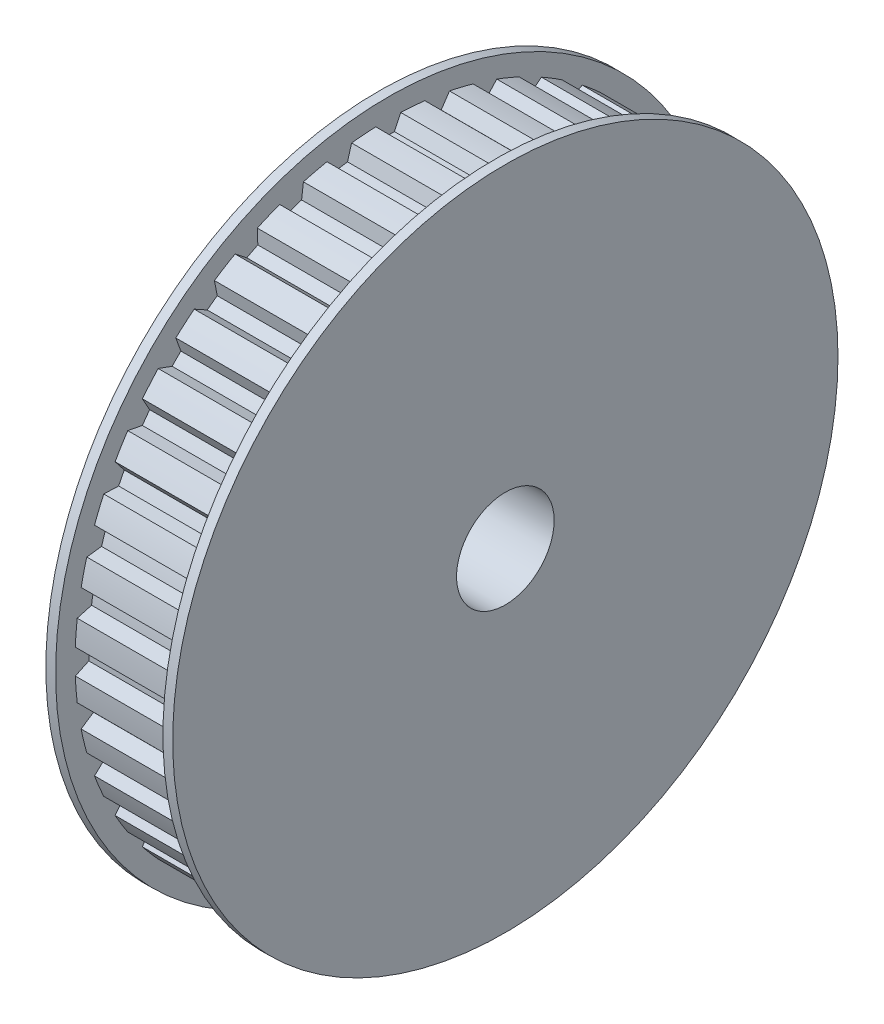
SolidWorks part; units mm, degrees
ref_plane "Front Plane" through (0, 0, 0) normal (0, 0, 1) x (1, 0, 0)
ref_plane "Top Plane" through (0, 0, 0) normal (0, 1, 0) x (1, 0, 0)
ref_plane "Right Plane" through (0, 0, 0) normal (1, 0, 0) x (0, 0, -1)
sketch "Sketch1" plane through (0, 0, 0) normal (1, 0, 0) x (0, 0, -1)
  line L0 (0, 32.085) -> (0, 0) construction
  circle A0 centre (0, 0) radius 32.085
  circle A1 centre (0, 0) radius 5
  point P19 (0, 0)
  dimension "D1" = 64.17
  dimension "D2" = 10
extrude "Boss-Extrude1" add sketch "Sketch1" along normal blind 11
sketch "Sketch2" plane through (0, 0, 0) normal (-1, 0, 0) x (0, 0, 1)
  line L0 (0, 0) -> (0, 32.085) construction
  line L1 (1.279, 32.0595) -> (0.635, 30.6784)
  line L2 (-1.279, 32.0595) -> (-0.635, 30.6784)
  line L3 (6.2784, 31.4647) -> (5.4263, 30.2014)
  line L4 (3.752, 31.8649) -> (4.172, 30.4001)
  line L5 (11.1233, 30.0952) -> (10.084, 28.9807)
  line L6 (8.6906, 30.8856) -> (8.8763, 29.3731)
  line L7 (15.6943, 27.9846) -> (14.4935, 27.0464)
  line L8 (13.4151, 29.1459) -> (13.362, 27.6229)
  line L9 (19.8788, 25.1849) -> (18.546, 24.4462)
  line L10 (17.8094, 26.6884) -> (17.5186, 25.1926)
  line L11 (23.5738, 21.7651) -> (22.1419, 21.2439)
  line L12 (21.7651, 23.5738) -> (21.2439, 22.1419)
  line L13 (26.6884, 17.8094) -> (25.1926, 17.5186)
  line L14 (25.1849, 19.8788) -> (24.4462, 18.546)
  line L15 (29.1459, 13.4151) -> (27.6229, 13.362)
  line L16 (27.9846, 15.6943) -> (27.0464, 14.4935)
  line L17 (30.8856, 8.6906) -> (29.3731, 8.8763)
  line L18 (30.0952, 11.1233) -> (28.9807, 10.084)
  line L19 (31.8649, 3.752) -> (30.4001, 4.172)
  line L20 (31.4647, 6.2784) -> (30.2014, 5.4263)
  line L21 (32.0595, -1.279) -> (30.6784, -0.635)
  line L22 (32.0595, 1.279) -> (30.6784, 0.635)
  line L23 (31.4647, -6.2784) -> (30.2014, -5.4263)
  line L24 (31.8649, -3.752) -> (30.4001, -4.172)
  line L25 (30.0952, -11.1233) -> (28.9807, -10.084)
  line L26 (30.8856, -8.6906) -> (29.3731, -8.8763)
  line L27 (27.9846, -15.6943) -> (27.0464, -14.4935)
  line L28 (29.1459, -13.4151) -> (27.6229, -13.362)
  line L29 (25.1849, -19.8788) -> (24.4462, -18.546)
  line L30 (26.6884, -17.8094) -> (25.1926, -17.5186)
  line L31 (21.7651, -23.5738) -> (21.2439, -22.1419)
  line L32 (23.5738, -21.7651) -> (22.1419, -21.2439)
  line L33 (17.8094, -26.6884) -> (17.5186, -25.1926)
  line L34 (19.8788, -25.1849) -> (18.546, -24.4462)
  line L35 (13.4151, -29.1459) -> (13.362, -27.6229)
  line L36 (15.6943, -27.9846) -> (14.4935, -27.0464)
  line L37 (8.6906, -30.8856) -> (8.8763, -29.3731)
  line L38 (11.1233, -30.0952) -> (10.084, -28.9807)
  line L39 (3.752, -31.8649) -> (4.172, -30.4001)
  line L40 (6.2784, -31.4647) -> (5.4263, -30.2014)
  line L41 (-1.279, -32.0595) -> (-0.635, -30.6784)
  line L42 (1.279, -32.0595) -> (0.635, -30.6784)
  line L43 (-6.2784, -31.4647) -> (-5.4263, -30.2014)
  line L44 (-3.752, -31.8649) -> (-4.172, -30.4001)
  line L45 (-11.1233, -30.0952) -> (-10.084, -28.9807)
  line L46 (-8.6906, -30.8856) -> (-8.8763, -29.3731)
  line L47 (-15.6943, -27.9846) -> (-14.4935, -27.0464)
  line L48 (-13.4151, -29.1459) -> (-13.362, -27.6229)
  line L49 (-19.8788, -25.1849) -> (-18.546, -24.4462)
  line L50 (-17.8094, -26.6884) -> (-17.5186, -25.1926)
  line L51 (-23.5738, -21.7651) -> (-22.1419, -21.2439)
  line L52 (-21.7651, -23.5738) -> (-21.2439, -22.1419)
  line L53 (-26.6884, -17.8094) -> (-25.1926, -17.5186)
  line L54 (-25.1849, -19.8788) -> (-24.4462, -18.546)
  line L55 (-29.1459, -13.4151) -> (-27.6229, -13.362)
  line L56 (-27.9846, -15.6943) -> (-27.0464, -14.4935)
  line L57 (-30.8856, -8.6906) -> (-29.3731, -8.8763)
  line L58 (-30.0952, -11.1233) -> (-28.9807, -10.084)
  line L59 (-31.8649, -3.752) -> (-30.4001, -4.172)
  line L60 (-31.4647, -6.2784) -> (-30.2014, -5.4263)
  line L61 (-32.0595, 1.279) -> (-30.6784, 0.635)
  line L62 (-32.0595, -1.279) -> (-30.6784, -0.635)
  line L63 (-31.4647, 6.2784) -> (-30.2014, 5.4263)
  line L64 (-31.8649, 3.752) -> (-30.4001, 4.172)
  line L65 (-30.0952, 11.1233) -> (-28.9807, 10.084)
  line L66 (-30.8856, 8.6906) -> (-29.3731, 8.8763)
  line L67 (-27.9846, 15.6943) -> (-27.0464, 14.4935)
  line L68 (-29.1459, 13.4151) -> (-27.6229, 13.362)
  line L69 (-25.1849, 19.8788) -> (-24.4462, 18.546)
  line L70 (-26.6884, 17.8094) -> (-25.1926, 17.5186)
  line L71 (-21.7651, 23.5738) -> (-21.2439, 22.1419)
  line L72 (-23.5738, 21.7651) -> (-22.1419, 21.2439)
  line L73 (-17.8094, 26.6884) -> (-17.5186, 25.1926)
  line L74 (-19.8788, 25.1849) -> (-18.546, 24.4462)
  line L75 (-13.4151, 29.1459) -> (-13.362, 27.6229)
  line L76 (-15.6943, 27.9846) -> (-14.4935, 27.0464)
  line L77 (-8.6906, 30.8856) -> (-8.8763, 29.3731)
  line L78 (-11.1233, 30.0952) -> (-10.084, 28.9807)
  line L79 (-3.752, 31.8649) -> (-4.172, 30.4001)
  line L80 (-6.2784, 31.4647) -> (-5.4263, 30.2014)
  circle A0 centre (0, 0) radius 32.085 construction
  arc A1 (1.279, 32.0595) -> (-1.279, 32.0595) centre (0, 0) ccw
  arc A2 (0.635, 30.6784) -> (-0.635, 30.6784) centre (0, 0) ccw
  arc A3 (6.2784, 31.4647) -> (3.752, 31.8649) centre (0, 0) ccw
  arc A4 (5.4263, 30.2014) -> (4.172, 30.4001) centre (0, 0) ccw
  arc A5 (11.1233, 30.0952) -> (8.6906, 30.8856) centre (0, 0) ccw
  arc A6 (10.084, 28.9807) -> (8.8763, 29.3731) centre (0, 0) ccw
  arc A7 (15.6943, 27.9846) -> (13.4151, 29.1459) centre (0, 0) ccw
  arc A8 (14.4935, 27.0464) -> (13.362, 27.6229) centre (0, 0) ccw
  arc A9 (19.8788, 25.1849) -> (17.8094, 26.6884) centre (0, 0) ccw
  arc A10 (18.546, 24.4462) -> (17.5186, 25.1926) centre (0, 0) ccw
  arc A11 (23.5738, 21.7651) -> (21.7651, 23.5738) centre (0, 0) ccw
  arc A12 (22.1419, 21.2439) -> (21.2439, 22.1419) centre (0, 0) ccw
  arc A13 (26.6884, 17.8094) -> (25.1849, 19.8788) centre (0, 0) ccw
  arc A14 (25.1926, 17.5186) -> (24.4462, 18.546) centre (0, 0) ccw
  arc A15 (29.1459, 13.4151) -> (27.9846, 15.6943) centre (0, 0) ccw
  arc A16 (27.6229, 13.362) -> (27.0464, 14.4935) centre (0, 0) ccw
  arc A17 (30.8856, 8.6906) -> (30.0952, 11.1233) centre (0, 0) ccw
  arc A18 (29.3731, 8.8763) -> (28.9807, 10.084) centre (0, 0) ccw
  arc A19 (31.8649, 3.752) -> (31.4647, 6.2784) centre (0, 0) ccw
  arc A20 (30.4001, 4.172) -> (30.2014, 5.4263) centre (0, 0) ccw
  arc A21 (32.0595, -1.279) -> (32.0595, 1.279) centre (0, 0) ccw
  arc A22 (30.6784, -0.635) -> (30.6784, 0.635) centre (0, 0) ccw
  arc A23 (31.4647, -6.2784) -> (31.8649, -3.752) centre (0, 0) ccw
  arc A24 (30.2014, -5.4263) -> (30.4001, -4.172) centre (0, 0) ccw
  arc A25 (30.0952, -11.1233) -> (30.8856, -8.6906) centre (0, 0) ccw
  arc A26 (28.9807, -10.084) -> (29.3731, -8.8763) centre (0, 0) ccw
  arc A27 (27.9846, -15.6943) -> (29.1459, -13.4151) centre (0, 0) ccw
  arc A28 (27.0464, -14.4935) -> (27.6229, -13.362) centre (0, 0) ccw
  arc A29 (25.1849, -19.8788) -> (26.6884, -17.8094) centre (0, 0) ccw
  arc A30 (24.4462, -18.546) -> (25.1926, -17.5186) centre (0, 0) ccw
  arc A31 (21.7651, -23.5738) -> (23.5738, -21.7651) centre (0, 0) ccw
  arc A32 (21.2439, -22.1419) -> (22.1419, -21.2439) centre (0, 0) ccw
  arc A33 (17.8094, -26.6884) -> (19.8788, -25.1849) centre (0, 0) ccw
  arc A34 (17.5186, -25.1926) -> (18.546, -24.4462) centre (0, 0) ccw
  arc A35 (13.4151, -29.1459) -> (15.6943, -27.9846) centre (0, 0) ccw
  arc A36 (13.362, -27.6229) -> (14.4935, -27.0464) centre (0, 0) ccw
  arc A37 (8.6906, -30.8856) -> (11.1233, -30.0952) centre (0, 0) ccw
  arc A38 (8.8763, -29.3731) -> (10.084, -28.9807) centre (0, 0) ccw
  arc A39 (3.752, -31.8649) -> (6.2784, -31.4647) centre (0, 0) ccw
  arc A40 (4.172, -30.4001) -> (5.4263, -30.2014) centre (0, 0) ccw
  arc A41 (-1.279, -32.0595) -> (1.279, -32.0595) centre (0, 0) ccw
  arc A42 (-0.635, -30.6784) -> (0.635, -30.6784) centre (0, 0) ccw
  arc A43 (-6.2784, -31.4647) -> (-3.752, -31.8649) centre (0, 0) ccw
  arc A44 (-5.4263, -30.2014) -> (-4.172, -30.4001) centre (0, 0) ccw
  arc A45 (-11.1233, -30.0952) -> (-8.6906, -30.8856) centre (0, 0) ccw
  arc A46 (-10.084, -28.9807) -> (-8.8763, -29.3731) centre (0, 0) ccw
  arc A47 (-15.6943, -27.9846) -> (-13.4151, -29.1459) centre (0, 0) ccw
  arc A48 (-14.4935, -27.0464) -> (-13.362, -27.6229) centre (0, 0) ccw
  arc A49 (-19.8788, -25.1849) -> (-17.8094, -26.6884) centre (0, 0) ccw
  arc A50 (-18.546, -24.4462) -> (-17.5186, -25.1926) centre (0, 0) ccw
  arc A51 (-23.5738, -21.7651) -> (-21.7651, -23.5738) centre (0, 0) ccw
  arc A52 (-22.1419, -21.2439) -> (-21.2439, -22.1419) centre (0, 0) ccw
  arc A53 (-26.6884, -17.8094) -> (-25.1849, -19.8788) centre (0, 0) ccw
  arc A54 (-25.1926, -17.5186) -> (-24.4462, -18.546) centre (0, 0) ccw
  arc A55 (-29.1459, -13.4151) -> (-27.9846, -15.6943) centre (0, 0) ccw
  arc A56 (-27.6229, -13.362) -> (-27.0464, -14.4935) centre (0, 0) ccw
  arc A57 (-30.8856, -8.6906) -> (-30.0952, -11.1233) centre (0, 0) ccw
  arc A58 (-29.3731, -8.8763) -> (-28.9807, -10.084) centre (0, 0) ccw
  arc A59 (-31.8649, -3.752) -> (-31.4647, -6.2784) centre (0, 0) ccw
  arc A60 (-30.4001, -4.172) -> (-30.2014, -5.4263) centre (0, 0) ccw
  arc A61 (-32.0595, 1.279) -> (-32.0595, -1.279) centre (0, 0) ccw
  arc A62 (-30.6784, 0.635) -> (-30.6784, -0.635) centre (0, 0) ccw
  arc A63 (-31.4647, 6.2784) -> (-31.8649, 3.752) centre (0, 0) ccw
  arc A64 (-30.2014, 5.4263) -> (-30.4001, 4.172) centre (0, 0) ccw
  arc A65 (-30.0952, 11.1233) -> (-30.8856, 8.6906) centre (0, 0) ccw
  arc A66 (-28.9807, 10.084) -> (-29.3731, 8.8763) centre (0, 0) ccw
  arc A67 (-27.9846, 15.6943) -> (-29.1459, 13.4151) centre (0, 0) ccw
  arc A68 (-27.0464, 14.4935) -> (-27.6229, 13.362) centre (0, 0) ccw
  arc A69 (-25.1849, 19.8788) -> (-26.6884, 17.8094) centre (0, 0) ccw
  arc A70 (-24.4462, 18.546) -> (-25.1926, 17.5186) centre (0, 0) ccw
  arc A71 (-21.7651, 23.5738) -> (-23.5738, 21.7651) centre (0, 0) ccw
  arc A72 (-21.2439, 22.1419) -> (-22.1419, 21.2439) centre (0, 0) ccw
  arc A73 (-17.8094, 26.6884) -> (-19.8788, 25.1849) centre (0, 0) ccw
  arc A74 (-17.5186, 25.1926) -> (-18.546, 24.4462) centre (0, 0) ccw
  arc A75 (-13.4151, 29.1459) -> (-15.6943, 27.9846) centre (0, 0) ccw
  arc A76 (-13.362, 27.6229) -> (-14.4935, 27.0464) centre (0, 0) ccw
  arc A77 (-8.6906, 30.8856) -> (-11.1233, 30.0952) centre (0, 0) ccw
  arc A78 (-8.8763, 29.3731) -> (-10.084, 28.9807) centre (0, 0) ccw
  arc A79 (-3.752, 31.8649) -> (-6.2784, 31.4647) centre (0, 0) ccw
  arc A80 (-4.172, 30.4001) -> (-5.4263, 30.2014) centre (0, 0) ccw
  point P10 (0, 30.685)
  point P18 (4.8002, 30.3072)
  point P23 (9.4822, 29.1832)
  point P28 (13.9307, 27.3405)
  point P33 (18.0362, 24.8247)
  point P38 (21.6976, 21.6976)
  point P43 (24.8247, 18.0362)
  point P48 (27.3405, 13.9307)
  point P53 (29.1832, 9.4822)
  point P58 (30.3072, 4.8002)
  point P63 (30.685, 0)
  point P68 (30.3072, -4.8002)
  point P73 (29.1832, -9.4822)
  point P78 (27.3405, -13.9307)
  point P83 (24.8247, -18.0362)
  point P88 (21.6976, -21.6976)
  point P93 (18.0362, -24.8247)
  point P98 (13.9307, -27.3405)
  point P103 (9.4822, -29.1832)
  point P108 (4.8002, -30.3072)
  point P113 (0, -30.685)
  point P118 (-4.8002, -30.3072)
  point P123 (-9.4822, -29.1832)
  point P128 (-13.9307, -27.3405)
  point P133 (-18.0362, -24.8247)
  point P138 (-21.6976, -21.6976)
  point P143 (-24.8247, -18.0362)
  point P148 (-27.3405, -13.9307)
  point P153 (-29.1832, -9.4822)
  point P158 (-30.3072, -4.8002)
  point P159 (0, 0)
  point P161 (-30.685, 0)
  point P166 (-30.3072, 4.8002)
  point P171 (-29.1832, 9.4822)
  point P176 (-27.3405, 13.9307)
  point P181 (-24.8247, 18.0362)
  point P186 (-21.6976, 21.6976)
  point P191 (-18.0362, 24.8247)
  point P196 (-13.9307, 27.3405)
  point P201 (-9.4822, 29.1832)
  point P206 (-4.8002, 30.3072)
  dimension "D1" = 1.4
  dimension "D2" = 25
  dimension "D3" = 0.635
  dimension "D4" = 40
extrude "Cut-Extrude1" cut sketch "Sketch2" against normal through all
sketch "Sketch4" plane through (11, 0, 0) normal (1, 0, 0) x (0, 0, -1)
  circle A0 centre (0, 0) radius 34.085
  circle A1 centre (0, 0) radius 5 construction
  circle A2 centre (0, 0) radius 5
  arc A3 (3.752, 31.8649) -> (1.279, 32.0595) centre (0, 0) ccw construction
  dimension "D1" = 2
extrude "Boss-Extrude2" add sketch "Sketch4" along normal blind 1
pattern_linear "LPattern1" count 2 spacing 12 along (-1, 0, 0) of "Boss-Extrude2"
